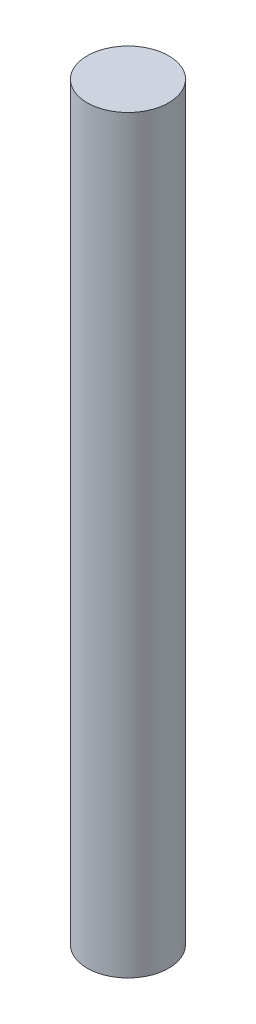
SolidWorks part; units mm, degrees
ref_plane "Front Plane" through (0, 0, 0) normal (0, 0, 1) x (1, 0, 0)
ref_plane "Top Plane" through (0, 0, 0) normal (0, 1, 0) x (1, 0, 0)
ref_plane "Right Plane" through (0, 0, 0) normal (1, 0, 0) x (0, 0, -1)
sketch "Sketch1" plane through (0, 0, 0) normal (0, 1, 0) x (1, 0, 0)
  circle A0 centre (0, 0) radius 2.5
  dimension "D1" = 5
extrude "Boss-Extrude1" add sketch "Sketch1" along normal blind 46
equation "\"Rod Diameter\"= 5mm"
equation "\"Rod Length\"= 46mm"
equation "\"D1@Boss-Extrude1\"=\"Rod Length\""
